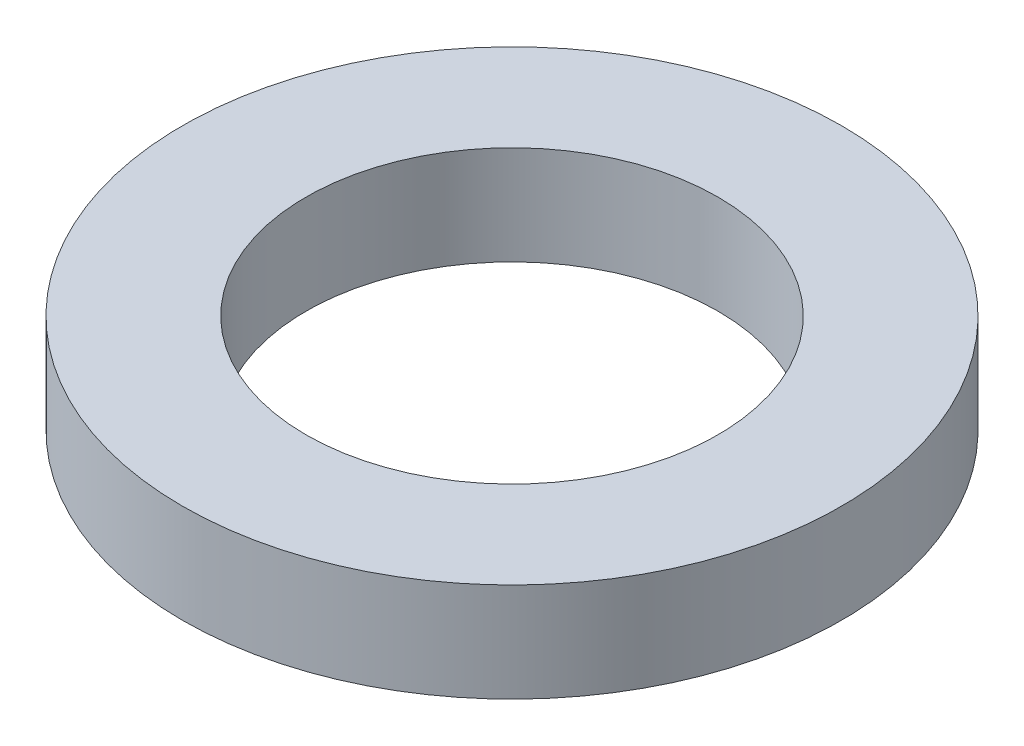
SolidWorks part; units mm, degrees
ref_plane "Front" through (0, 0, 0) normal (0, 0, 1) x (1, 0, 0)
ref_plane "Top" through (0, 0, 0) normal (0, 1, 0) x (1, 0, 0)
ref_plane "Right" through (0, 0, 0) normal (1, 0, 0) x (0, 0, -1)
sketch "Sketch1" plane through (0, 0, 0) normal (0, 1, 0) x (1, 0, 0)
  circle A0 centre (0, 0) radius 2
  circle A1 centre (0, 0) radius 1.25
  dimension "D1" = 4
  dimension "D2" = 2.5
extrude "Boss-Extrude1" add sketch "Sketch1" along normal blind 0.6
